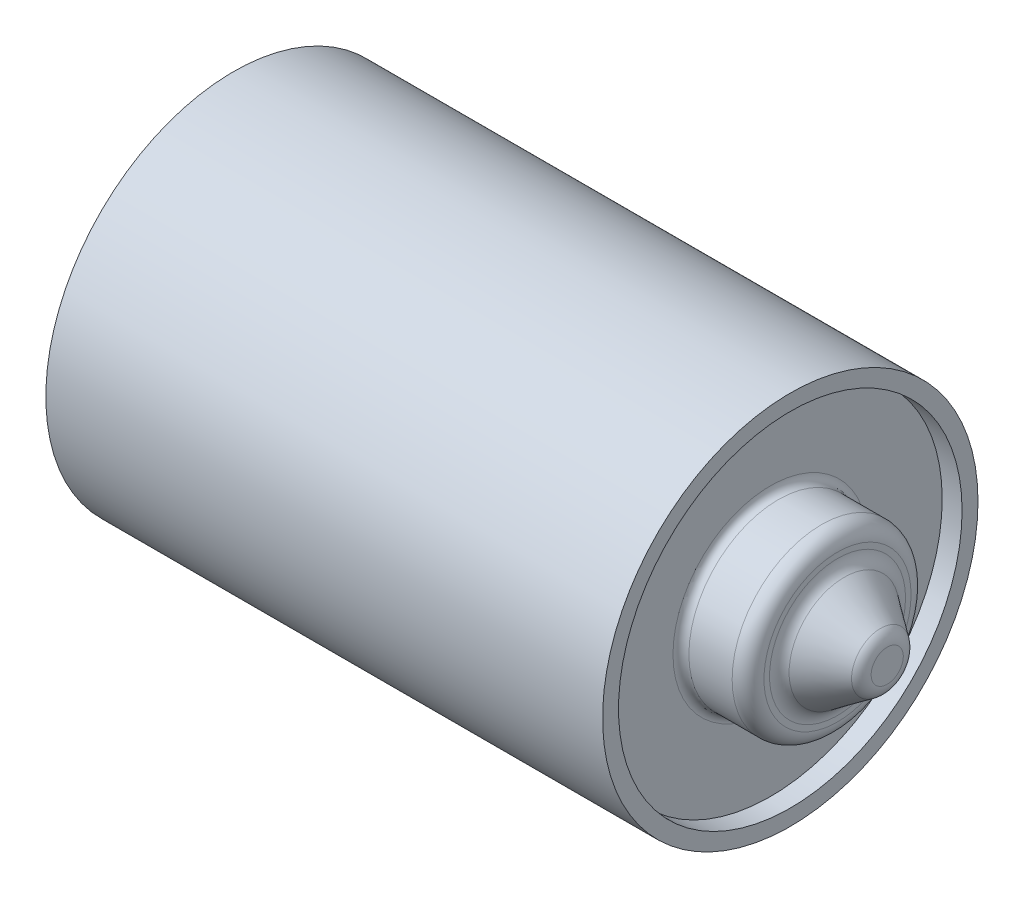
SolidWorks part; units mm, degrees
ref_plane "Front Plane" through (0, 0, 0) normal (0, 0, 1) x (1, 0, 0)
ref_plane "Top Plane" through (0, 0, 0) normal (0, 1, 0) x (1, 0, 0)
ref_plane "Right Plane" through (0, 0, 0) normal (1, 0, 0) x (0, 0, -1)
ref_plane "Plane1" through (0, 0, 38.1099) normal (0, 0, 1) x (1, 0, 0)
sketch "Sketch1" plane through (0, 0, 38.1099) normal (0, 0, 1) x (1, 0, 0)
  line L0 (670.548, 86.7925) -> (670.548, 56.8205)
  line L1 (670.548, 56.8205) -> (774.9268, 56.8205)
  line L2 (774.9268, 56.8205) -> (774.9268, 59.3884)
  line L3 (773.865, 61.4539) -> (768.0511, 65.6145)
  line L4 (766.9893, 67.6801) -> (766.9893, 68.568)
  line L5 (764.4493, 71.108) -> (757.543, 71.108)
  line L6 (756.273, 72.378) -> (756.273, 84.2525)
  line L7 (756.273, 84.2525) -> (759.448, 84.2525)
  line L8 (759.448, 84.2525) -> (759.448, 86.7925)
  line L9 (759.448, 86.7925) -> (670.548, 86.7925)
  line L10 (670.548, 56.8205) -> (774.9295, 56.8205) construction
  arc A0 (774.9268, 59.3884) -> (773.865, 61.4539) centre (772.3868, 59.3884) ccw
  arc A1 (768.0511, 65.6145) -> (766.9893, 67.6801) centre (769.5293, 67.6801) cw
  arc A2 (766.9893, 68.568) -> (764.4493, 71.108) centre (764.4493, 68.568) ccw
  arc A3 (757.543, 71.108) -> (756.273, 72.378) centre (757.543, 72.378) cw
revolve "Revolve1" add sketch "Sketch1" angle 360 about L10
